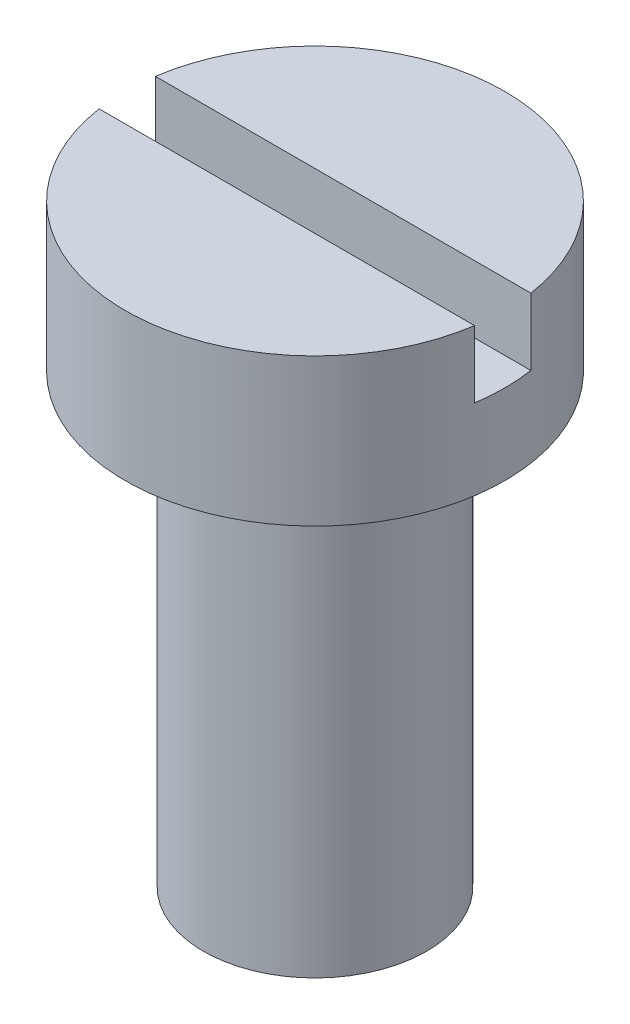
SolidWorks part; units mm, degrees
ref_plane "Спереди" through (0, 0, 0) normal (0, 0, 1) x (1, 0, 0)
ref_plane "Сверху" through (0, 0, 0) normal (0, 1, 0) x (1, 0, 0)
ref_plane "Справа" through (0, 0, 0) normal (1, 0, 0) x (0, 0, -1)
sketch "Эскиз1" plane through (0, 0, 0) normal (0, 0, 1) x (1, 0, 0)
  line L0 (0, 0) -> (0, 8.8731) construction
  line L1 (0, 0) -> (2.5, 0)
  line L2 (2.5, 0) -> (2.5, 10)
  line L3 (2.5, 10) -> (4.25, 10)
  line L4 (4.25, 10) -> (4.25, 13.3)
  line L5 (4.25, 13.3) -> (0, 13.3)
  line L6 (0, 0) -> (0, 13.3)
  dimension "D1" = 5
  dimension "D2" = 8.5
  dimension "D3" = 3.3
  dimension "D4" = 10
revolve "Основание-Повернуть" add sketch "Эскиз1" angle 360 about L0
cosmetic thread "Условное изображение резьбы1" parameters "D1"=8, "D2"=3
sketch "Эскиз2" plane through (0, 13.3, 0) normal (0, 1, 0) x (-1, 0, 0)
  line L0 (1.1491, 0) -> (-1.1873, 0) construction
  line L1 (-4.203, -0.63) -> (4.203, -0.63)
  line L2 (-4.203, 0.63) -> (4.203, 0.63)
  circle A0 centre (0, 0) radius 4.25 construction
  arc A1 (-4.203, 0.63) -> (-4.203, -0.63) centre (0, 0) ccw
  arc A2 (4.203, -0.63) -> (4.203, 0.63) centre (0, 0) ccw
  dimension "D1" = 1.26
extrude "Вырез-Вытянуть1" cut sketch "Эскиз2" against normal blind 1.5
